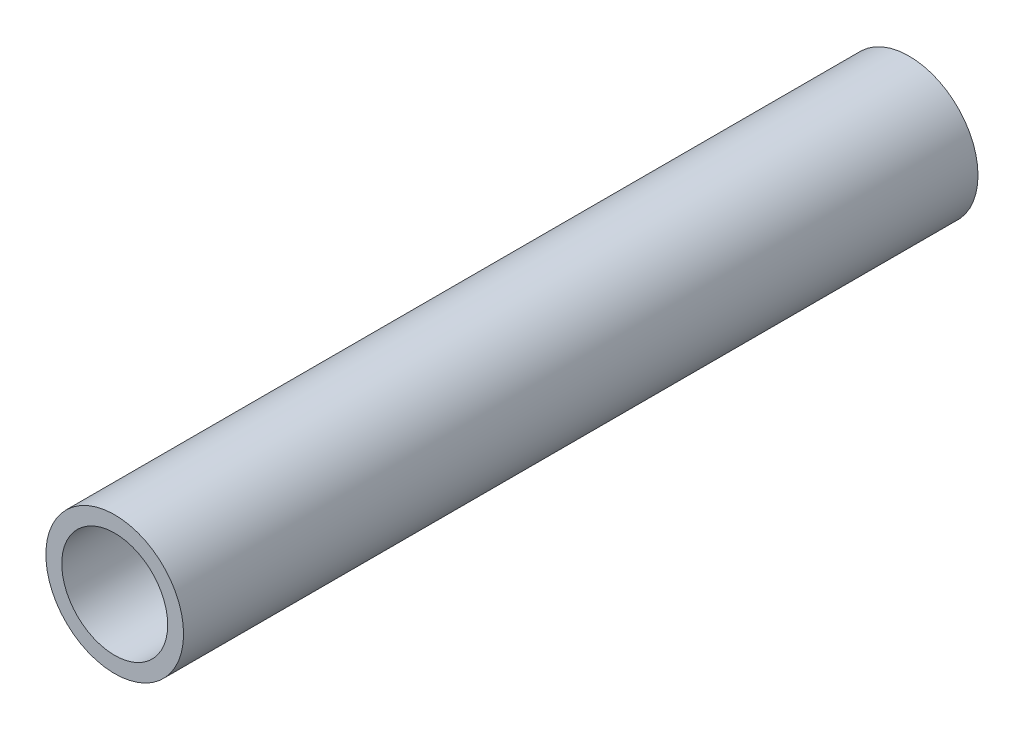
SolidWorks part; units mm, degrees
ref_plane "Front Plane" through (0, 0, 0) normal (0, 0, 1) x (1, 0, 0)
ref_plane "Top Plane" through (0, 0, 0) normal (0, 1, 0) x (1, 0, 0)
ref_plane "Right Plane" through (0, 0, 0) normal (1, 0, 0) x (0, 0, -1)
sketch "Sketch1" plane through (0, 0, 0) normal (0, 0, 1) x (1, 0, 0)
  circle A0 centre (0, 0) radius 16.51
  circle A1 centre (0, 0) radius 12.7
  dimension "D1" = 33.02
  dimension "D2" = 25.4
extrude "Boss-Extrude1" add sketch "Sketch1" along normal blind 190.5
ref_plane "Fitting2" through (0, 0, 190.5) normal (0, 0, 1) x (1, 0, 0)
ref_plane "Fitting1" through (0, 0, 0) normal (0, 0, 1) x (1, 0, 0)
